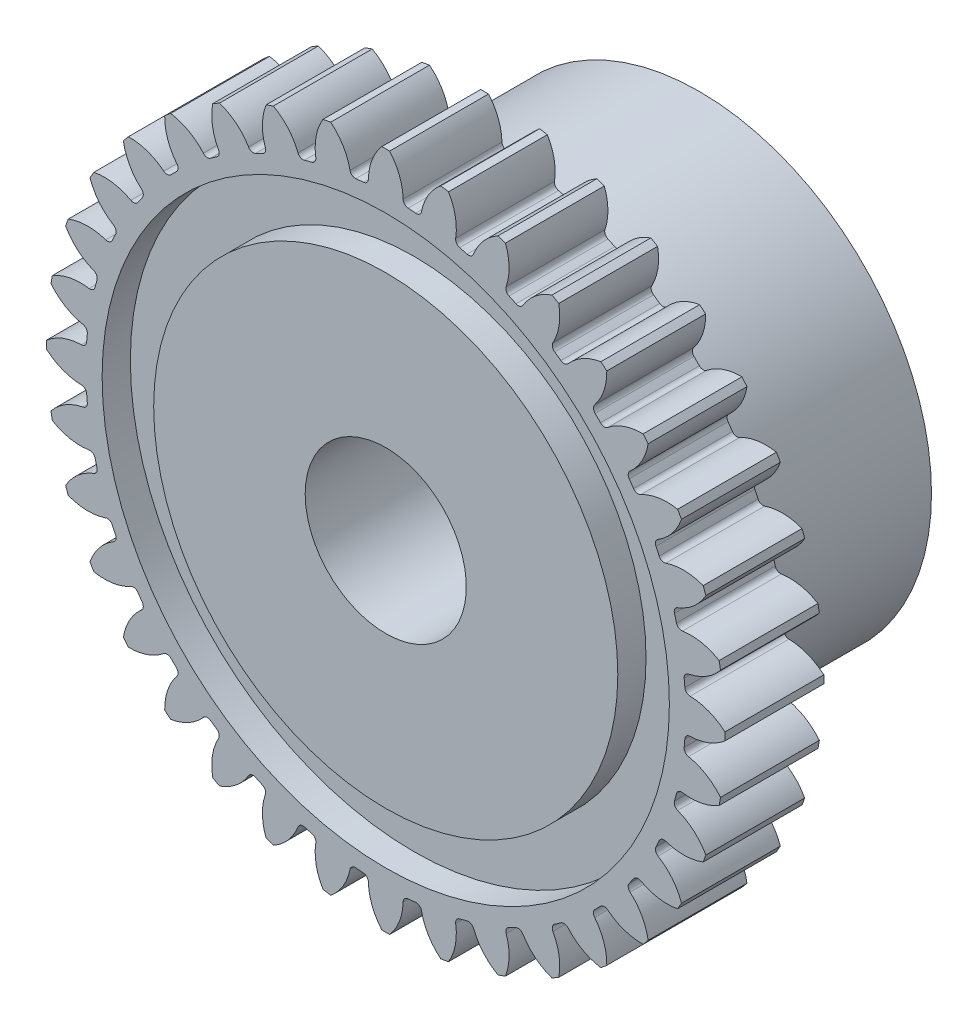
SolidWorks part; units mm, degrees
ref_plane "Front Plane" through (0, 0, 0) normal (0, 0, 1) x (1, 0, 0)
ref_plane "Top Plane" through (0, 0, 0) normal (0, 1, 0) x (1, 0, 0)
ref_plane "Right Plane" through (0, 0, 0) normal (1, 0, 0) x (0, 0, -1)
sketch "Sketch1" plane through (0, 0, 0) normal (1, 0, 0) x (0, 0, -1)
  line L0 (-4.6355, 0) -> (-4.6355, 10.026)
  line L1 (-4.6355, 10.026) -> (-1.7145, 10.026)
  line L2 (-1.7145, 10.026) -> (-1.7145, 6.858)
  line L3 (-1.7145, 6.858) -> (4.6355, 6.858)
  line L4 (4.6355, 6.858) -> (4.6355, 0)
  line L5 (4.6355, 0) -> (-4.6355, 0) construction
  line L6 (-4.6355, 2.3812) -> (4.6355, 2.3812)
  point P9 (-4.6355, 8.382)
  dimension "OD" = 20.052
  dimension "Face Width" = 2.921
  dimension "Hub Width" = 6.35
  dimension "Hub Diameter" = 13.716
  dimension "For Shaft Diameter" = 4.7625
  dimension "Overall Width" = 9.271
  dimension "Under Cut Diameter" = 16.764
sketch "Sketch2" plane through (0, 0, 0) normal (0, 0, 1) x (1, 0, 0)
  line L0 (-0.6621, 8.8388) -> (-0.23, 10.026)
  line L1 (-0.23, 10.026) -> (0.23, 10.026)
  line L2 (0.23, 10.026) -> (0.6621, 8.8388)
  line L3 (0, 10.026) -> (0, 0) construction
  line L4 (0, 0) -> (-0.8738, 9.9879) construction
  line L5 (0, 0) -> (0.8738, 9.9879) construction
  line L6 (-2.1868, 8.5895) -> (-1.9675, 9.8338)
  line L7 (-1.9675, 9.8338) -> (-1.5145, 9.9136)
  line L8 (-1.5145, 9.9136) -> (-0.8828, 8.8195)
  line L9 (-1.741, 9.8737) -> (0, 0) construction
  line L11 (-0.23, 10.026) -> (0, 10.026) construction
  line L12 (-0.4156, 9.5159) -> (0.4156, 9.5159) construction
  circle A0 centre (0, 0) radius 9.525 construction
  circle A2 centre (0, 0) radius 10.026
  circle A3 centre (0, 0) radius 8.8635
  arc A5 (-0.115, 10.026) -> (-0.5096, 8.8489) centre (1.1089, 8.961) ccw
  arc A6 (0.5096, 8.8489) -> (0.115, 10.026) centre (-1.1089, 8.961) ccw
  arc A7 (-1.0348, 8.8029) -> (-1.6278, 9.8937) centre (-2.6481, 8.6323) ccw
  arc A8 (-0.4156, 9.5159) -> (0.4156, 9.5159) centre (0, 0) cw
  point P3 (0, 9.525)
  point P5 (1.654, 9.3803)
  point P6 (-3.2577, -8.9506)
  point P9 (3.2577, 8.9506)
  point P10 (4.7625, 8.2489)
  point P11 (6.1226, 7.2966)
  point P12 (7.2966, 6.1226)
  point P13 (8.2489, 4.7625)
  point P14 (8.9506, 3.2577)
  point P15 (9.3803, 1.654)
  point P16 (9.525, 0)
  point P17 (9.3803, -1.654)
  point P18 (8.9506, -3.2577)
  point P19 (8.2489, -4.7625)
  point P20 (7.2966, -6.1226)
  point P21 (6.1226, -7.2966)
  point P22 (4.7625, -8.2489)
  point P23 (3.2577, -8.9506)
  point P24 (1.654, -9.3803)
  point P25 (0, -9.525)
  point P26 (-1.654, -9.3803)
  point P27 (-4.7625, -8.2489)
  point P28 (-6.1226, -7.2966)
  point P29 (-7.2966, -6.1226)
  point P30 (-8.2489, -4.7625)
  point P31 (0, 0)
  point P55 (-8.9506, -3.2577)
  point P56 (-9.3803, -1.654)
  point P57 (-9.525, 0)
  point P58 (-9.3803, 1.654)
  point P59 (-8.9506, 3.2577)
  point P61 (-8.2489, 4.7625)
  point P62 (-7.2966, 6.1226)
  point P63 (-6.1226, 7.2966)
  point P64 (-4.7625, 8.2489)
  point P65 (-3.2577, 8.9506)
  point P66 (-1.654, 9.3803)
  dimension "Gear Pitch Diameter" = 19.05
  dimension "Pressure Angle" = 20
  dimension "Addendum" = 0.501
  dimension "Dedendum" = 0.6615
  dimension "D1" = 10
  dimension "D2" = 0.8312
  dimension "Number of Teeth" = 36
sketch "Sketch3" plane through (0, 0, 0) normal (1, 0, 0) x (0, 0, -1)
  line L0 (-4.6355, 10.026) -> (-1.7145, 10.026) construction
  line L1 (4.6355, 6.858) -> (4.6355, 0) construction
  line L2 (-1.7145, 6.858) -> (4.6355, 6.858) construction
  line L3 (-1.7145, 10.026) -> (-1.7145, 6.858) construction
  line L4 (-4.6355, 0) -> (-4.6355, 10.026) construction
  line L5 (-4.6355, 2.3812) -> (4.6355, 2.3812) construction
  line L6 (-4.6355, 10.026) -> (-1.7145, 10.026)
  line L7 (4.6355, 6.858) -> (4.6355, 2.3812)
  line L8 (-4.6355, 6.858) -> (-3.8009, 6.858)
  line L9 (-1.7145, 10.026) -> (-1.7145, 8.382)
  line L10 (-4.6355, 2.3812) -> (-4.6355, 6.858)
  line L11 (-4.6355, 2.3812) -> (4.6355, 2.3812)
  line L12 (-4.6355, 8.382) -> (-3.8009, 8.382)
  line L13 (-3.8009, 8.382) -> (-3.8009, 6.858)
  line L14 (-1.7145, 8.382) -> (-2.5491, 8.382)
  line L15 (-2.5491, 8.382) -> (-2.5491, 6.858)
  line L16 (-2.5491, 6.858) -> (4.6355, 6.858)
  line L17 (-4.6355, 8.382) -> (-4.6355, 10.026)
  dimension "D1" = 0.8346
revolve "Revolve1" add sketch "Sketch3" angle 360 about L5
sketch "Sketch4" plane through (0, 0, 4.6355) normal (0, 0, 1) x (1, 0, 0)
  arc A1 (-0.115, 10.026) -> (-0.5096, 8.8489) centre (1.1089, 8.961) ccw construction
  arc A2 (-1.0348, 8.8029) -> (-1.6278, 9.8937) centre (-2.6481, 8.6323) ccw construction
  arc A3 (-0.1156, 10.0253) -> (-0.5131, 8.994) centre (1.1089, 8.961) ccw
  arc A4 (-1.0565, 8.9465) -> (-1.6271, 9.8931) centre (-2.6481, 8.6323) ccw
  circle A5 centre (0, 0) radius 10.026 construction
  arc A6 (-0.1156, 10.0253) -> (-1.6271, 9.8931) centre (0, 0) ccw
  circle A7 centre (0, 0) radius 8.8635 construction
  arc A8 (-0.66, 8.8389) -> (-0.8849, 8.8193) centre (0, 0) ccw
  arc A9 (-1.0565, 8.9465) -> (-0.8849, 8.8193) centre (-0.9007, 8.9772) ccw
  arc A10 (-0.66, 8.8389) -> (-0.5131, 8.994) centre (-0.6718, 8.9972) ccw
  dimension "D1" = 0.1587
extrude "Cut-Extrude1" cut sketch "Sketch4" against normal through all both and the other way through all
pattern_circular "CirPattern1" count 36 over 360 about axis through (0, 0, 0) along (0, 0, 1) of "Cut-Extrude1"
equation "\"Dedendum@Sketch2\" = 1.25 /  ( \"Number of Teeth@Sketch2\" / \"Gear Pitch Diameter@Sketch2\" ) "
equation "\"D1@Sketch2\"=360/\"Number of Teeth@Sketch2\""
equation "\"D1@Sketch4\"=.3/(\"Number of Teeth@Sketch2\"/\"Gear Pitch Diameter@Sketch2\")"
equation "\"D1@CirPattern1\"=\"Number of Teeth@Sketch2\""
equation "\"D2@Sketch2\"=1.5708/(\"Number of Teeth@Sketch2\"/\"Gear Pitch Diameter@Sketch2\")"
equation "\"D1@Sketch3\"=\"Face Width@Sketch1\"/3.5"
